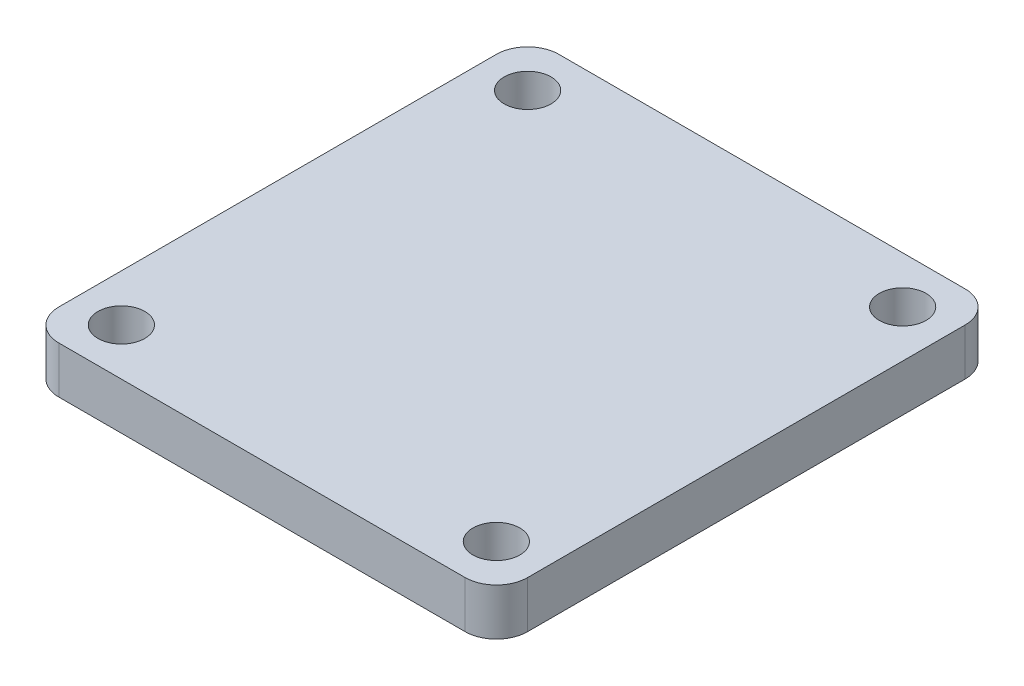
SolidWorks part; units mm, degrees
material "聚脂树脂"
ref_plane "前视基准面" through (0, 0, 0) normal (0, 0, 1) x (1, 0, 0)
ref_plane "上视基准面" through (0, 0, 0) normal (0, 1, 0) x (1, 0, 0)
ref_plane "右视基准面" through (0, 0, 0) normal (1, 0, 0) x (0, 0, -1)
other "Configuration Table"
sketch "草图1" plane through (0, 0, 0) normal (0, 1, 0) x (1, 0, 0)
  line L0 (0, 0) -> (0, 23.8245) construction
  line L1 (-15, -16) -> (15, -16)
  line L2 (-15, -16) -> (-15, 16)
  line L3 (-15, 16) -> (15, 16)
  line L4 (15, -16) -> (15, 16)
  line L5 (-15, -16) -> (15, 16) construction
  line L6 (-15, 16) -> (15, -16) construction
  line L7 (0, 0) -> (25.797, 0) construction
  circle A0 centre (12, 13) radius 1.5
  circle A1 centre (-12, 13) radius 1.5
  circle A2 centre (12, -13) radius 1.5
  circle A3 centre (-12, -13) radius 1.5
  point P0 (0, 0)
  dimension "D3" = 3
  dimension "D4" = 26
  dimension "D5" = 24
  dimension "D1" = 30
  dimension "D2" = 32
extrude "凸台-拉伸1" add sketch "草图1" along normal blind 3
fillet "圆角1" radius 2 4 edges at (-15, 1.5, -16) (-15, 1.5, 16) (15, 1.5, -16) (15, 1.5, 16)
